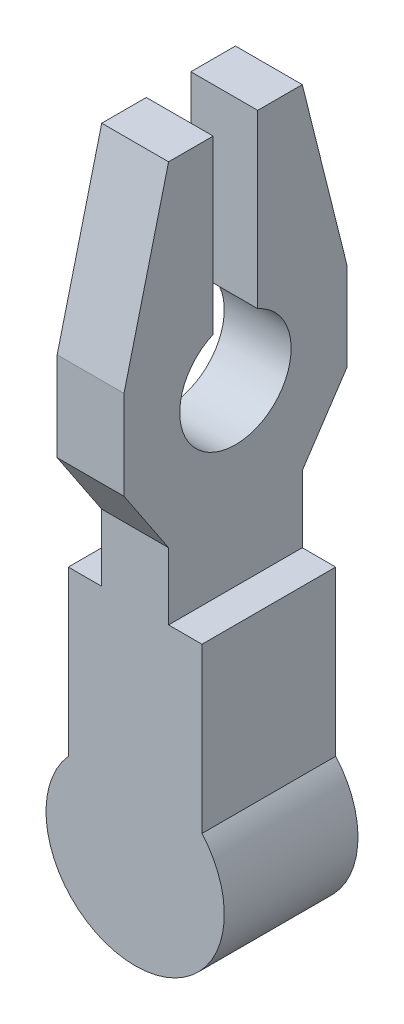
SolidWorks part; units mm, degrees
ref_plane "Alzado" through (0, 0, 0) normal (0, 0, 1) x (1, 0, 0)
ref_plane "Planta" through (0, 0, 0) normal (0, 1, 0) x (1, 0, 0)
ref_plane "Vista lateral" through (0, 0, 0) normal (1, 0, 0) x (0, 0, -1)
sketch "Croquis1" plane through (0, 0, 0) normal (0, 0, 1) x (1, 0, 0)
  circle A0 centre (0, 0) radius 40
  dimension "D1" = 80
extrude "Saliente-Extruir1" add sketch "Croquis1" along normal mid plane 60
sketch "Croquis2" plane through (0, 0, 0) normal (0, 0, 1) x (1, 0, 0)
  line L1 (-30, 0) -> (30, 0)
  line L2 (-30, 0) -> (-30, 100)
  line L3 (-30, 100) -> (30, 100)
  line L4 (30, 0) -> (30, 100)
  dimension "D1" = 60
  dimension "D2" = 100
extrude "Saliente-Extruir2" add sketch "Croquis2" along normal mid plane 60
sketch "Croquis3" plane through (0, 0, 0) normal (1, 0, 0) x (0, 0, -1)
  line L0 (0, 100) -> (0, 262.1953) construction
  line L1 (-30, 100) -> (30, 100) construction
  line L2 (-30, 130) -> (-30, 100)
  line L3 (10, 202.9129) -> (10, 280)
  line L4 (10, 280) -> (30, 280)
  line L5 (30, 280) -> (50, 200)
  line L6 (50, 200) -> (50, 160)
  line L7 (50, 160) -> (30, 130)
  line L8 (30, 130) -> (30, 100)
  line L9 (30, 100) -> (-30, 100)
  line L10 (-50, 160) -> (-30, 130)
  line L11 (-50, 200) -> (-50, 160)
  line L12 (-30, 280) -> (-50, 200)
  line L13 (-10, 280) -> (-30, 280)
  line L14 (-10, 202.9129) -> (-10, 280)
  arc A0 (-10, 202.9129) -> (10, 202.9129) centre (0, 180) ccw
  dimension "D3" = 25
  dimension "D1" = 20
  dimension "D2" = 180
  dimension "D4" = 100
  dimension "D5" = 20
  dimension "D6" = 100
  dimension "D7" = 80
  dimension "D8" = 30
  dimension "D9" = 120
extrude "Saliente-Extruir3" add sketch "Croquis3" along normal mid plane 30
